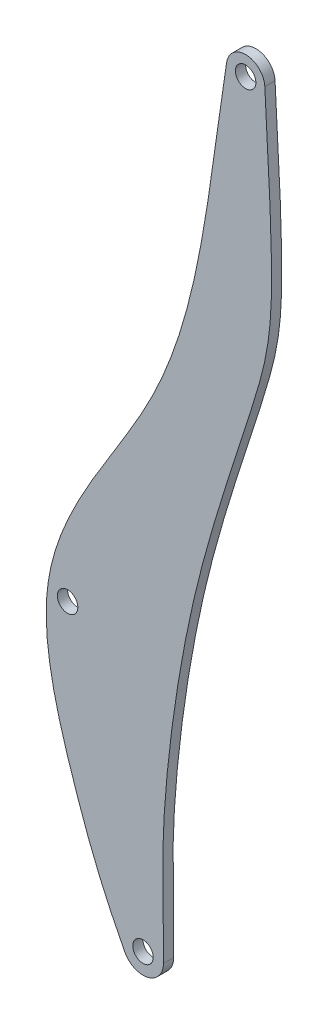
SolidWorks part; units mm, degrees
ref_plane "前视基准面" through (0, 0, 0) normal (0, 0, 1) x (1, 0, 0)
ref_plane "上视基准面" through (0, 0, 0) normal (0, 1, 0) x (1, 0, 0)
ref_plane "右视基准面" through (0, 0, 0) normal (1, 0, 0) x (0, 0, -1)
other "Configuration Table"
sketch "草图1" plane through (0, 0, 0) normal (0, 0, 1) x (1, 0, 0)
  line L0 (-90.2605, -156.5809) -> (83.574, 374.0716) construction
  line L1 (83.574, 374.0716) -> (-16.6281, -415.723) construction
  line L2 (-16.6281, -415.723) -> (-90.2605, -156.5809) construction
  circle A0 centre (83.574, 374.0716) radius 10
  circle A1 centre (-90.2605, -156.5809) radius 10
  circle A2 centre (-16.6281, -415.723) radius 10
  arc A3 (102.3112, 375.112) -> (65.0365, 376.991) centre (83.574, 374.0716) ccw
  arc A4 (-109.5262, -151.9362) -> (-110.0782, -156.5809) centre (-90.2605, -156.5809) ccw
  arc A5 (-34.1366, -425.3902) -> (3.3719, -415.7096) centre (-16.6281, -415.723) ccw
  spline S0 degree 3 poles (102.3112, 375.112) (112.2257, 196.5551) (112.5669, 154.3844) (23.6862, -90.7931) (0.0348, -297.2858) (3.3311, -354.8365) (3.3719, -415.7096) knots 0 0 0 0 0.332735 0.581142 0.871634 1 1 1 1
  spline S1 degree 3 poles (65.0365, 376.991) (45.8891, 252.9422) (35.5238, 78.6944) (-140.8079, -126.0227) (-84.8262, -308.6166) (-57.3312, -381.1806) (-34.1366, -425.3902) knots 0 0 0 0 0.394447 0.667711 0.855398 1 1 1 1
  dimension "D4" = 20
  dimension "D1" = 146
  dimension "D2" = 558.4
  dimension "D3" = 269.4
extrude "凸台-拉伸1" add sketch "草图1" along normal blind 10 contours A3 S1 A5 S0 A0 A1 A2
